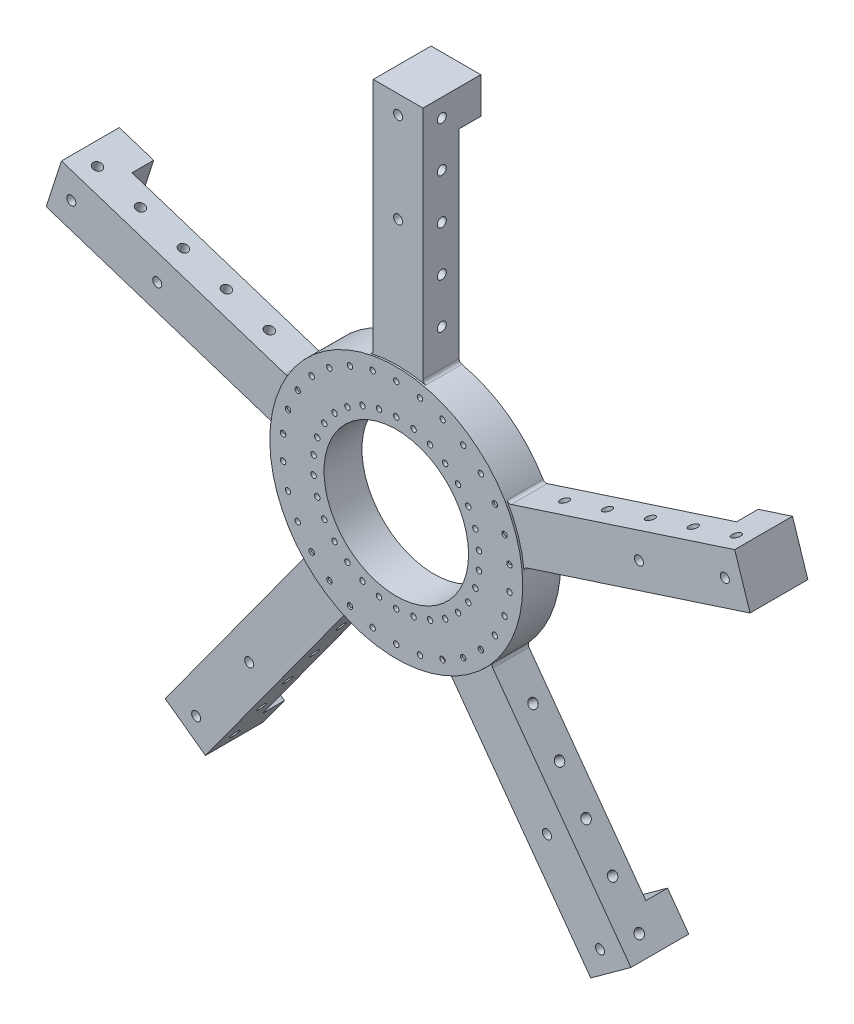
SolidWorks part; units mm, degrees
ref_plane "Ön Düzlem" through (0, 0, 0) normal (0, 0, 1) x (1, 0, 0)
ref_plane "Üst Düzlem" through (0, 0, 0) normal (0, 1, 0) x (1, 0, 0)
ref_plane "Sağ Düzlem" through (0, 0, 0) normal (1, 0, 0) x (0, 0, -1)
sketch "Sketch1" plane through (0, 0, 0) normal (0, 0, 1) x (1, 0, 0)
  circle A0 centre (0, 0) radius 400
  circle A1 centre (0, 0) radius 700
  dimension "D1" = 800
  dimension "D2" = 1400
extrude "Boss-Extrude1" add sketch "Sketch1" along normal blind 210
sketch "Sketch2" plane through (0, 0, 0) normal (0, 1, 0) x (1, 0, 0)
  line L0 (700, 0) -> (-700, 0) construction
  line L1 (-137.5, 0) -> (137.5, 0)
  line L2 (-137.5, 0) -> (-137.5, -200)
  line L3 (-137.5, -200) -> (137.5, -200)
  line L4 (137.5, 0) -> (137.5, -200)
  point P6 (0, 0)
  dimension "D1" = 200
  dimension "D2" = 275
extrude "Boss-Extrude2" add sketch "Sketch2" along normal blind 1443.6 from offset 560
sketch "Sketch3" plane through (0, 0, 0) normal (0, 0, -1) x (-1, 0, 0)
  line L0 (137.5, 2003.6) -> (137.5, 686.3627) construction
  line L1 (-137.5, 2003.6) -> (137.5, 2003.6)
  line L2 (-137.5, 2003.6) -> (-137.5, 1803.6)
  line L3 (-137.5, 1803.6) -> (137.5, 1803.6)
  line L4 (137.5, 2003.6) -> (137.5, 1803.6)
  dimension "D1" = 200
extrude "Boss-Extrude3" add sketch "Sketch3" along normal blind 120
sketch "Sketch4" plane through (0, 0, 210) normal (0, 0, 1) x (1, 0, 0)
  circle A0 centre (0, 630) radius 15
  circle A1 centre (0, 460) radius 15
  point P4 (0, 615.0014)
  point P5 (0, 471.5532)
  point P7 (0, 587.3301)
  point P8 (0, 586.3845)
  point P9 (-0.289, 73.9965)
  dimension "D1" = 30
  dimension "D2" = 460
  dimension "D3" = 630
extrude "Cut-Extrude1" cut sketch "Sketch4" against normal blind 75
pattern_circular "CirPattern1" count 30 over 360 about axis through (0, 0, 0) along (0, 0, 1) of "Cut-Extrude1"
sketch "Sketch6" plane through (-137.5, 0, 0) normal (-1, 0, 0) x (0, 0, 1)
  line L0 (-120, 1803.6) -> (-120, 2003.6) construction
  circle A0 centre (95.7556, 1903.6) radius 25
  circle A1 centre (95.7556, 1653.6) radius 25
  circle A2 centre (95.7556, 1403.6) radius 25
  circle A3 centre (95.7556, 1153.6) radius 25
  circle A4 centre (95.7556, 903.6) radius 25
  point P10 (0, 0)
  point P13 (-120, 1903.6)
  point P14 (0, 0)
  point P15 (0, 0)
  point P16 (0, 0)
  point P17 (0, 0)
  point P18 (0, 0)
  point P23 (0, 0)
  dimension "D5" = 50
  dimension "D1" = 250
  dimension "D2" = 250
  dimension "D3" = 250
  dimension "D4" = 250
extrude "Cut-Extrude3" cut sketch "Sketch6" against normal blind 75
sketch "Sketch5" plane through (0, 0, 200) normal (0, 0, 1) x (1, 0, 0)
  circle A0 centre (0, 1901.5861) radius 25
  circle A1 centre (0, 1401.6434) radius 25
  point P4 (0, 0)
  point P6 (0, 0)
  point P7 (0, 1893.1175)
  point P8 (0, 1901.5861)
  point P9 (0, 1401.6434)
  dimension "D2" = 50
extrude "Cut-Extrude2" cut sketch "Sketch5" against normal blind 75
mirror "Mirror1" about plane through (0, 0, 0) normal (1, 0, 0) of "Cut-Extrude3"
fillet "Fillet1" radius 20 2 edges at (137.5, 686.3627, 100) (-137.5, 686.3627, 100)
pattern_circular "CirPattern2" count 5 over 360 about axis through (0, 0, 0) along (0, 0, 1) of "Fillet1", "Mirror1", "Cut-Extrude2", "Cut-Extrude3", "Boss-Extrude2", "Boss-Extrude3"
